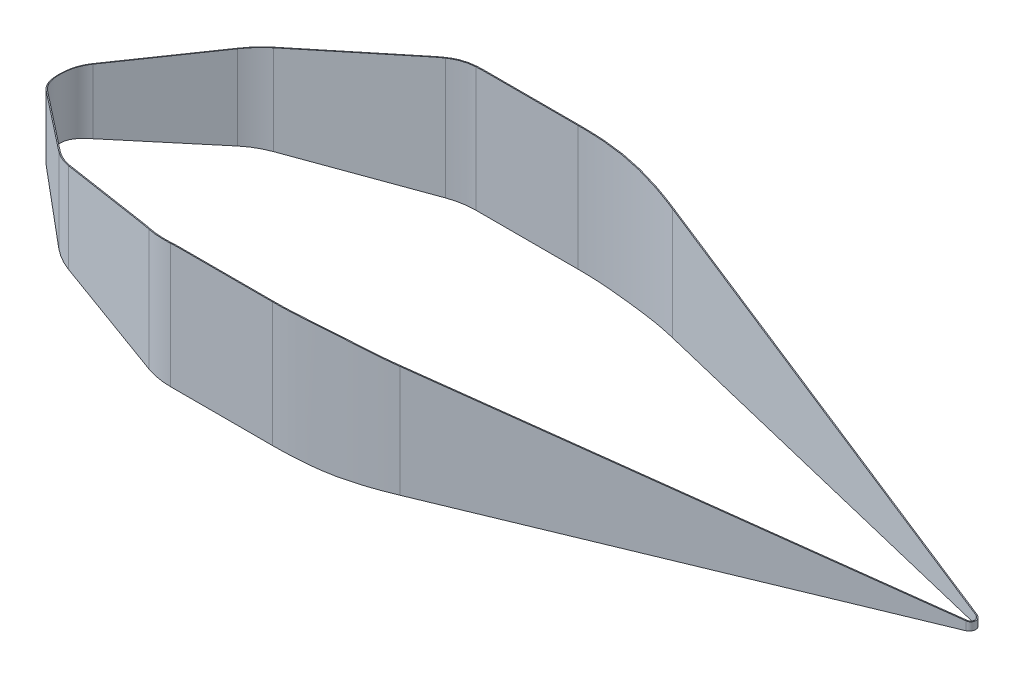
SolidWorks part; units mm, degrees
ref_plane "Front Plane" through (0, 0, 0) normal (0, 0, 1) x (1, 0, 0)
ref_plane "Top Plane" through (0, 0, 0) normal (0, 1, 0) x (1, 0, 0)
ref_plane "Right Plane" through (0, 0, 0) normal (1, 0, 0) x (0, 0, -1)
sketch "Sketch1" plane through (0, 0, 0) normal (0, 1, 0) x (1, 0, 0)
  line L0 (146.0698, 122.5671) -> (556.1483, 466.6637)
  line L1 (676.4552, 536.1229) -> (1335.1737, 775.877)
  line L2 (1471.9818, 800) -> (2005.9909, 800)
  line L3 (2584.2902, 714.5678) -> (4854.922, 28.7185)
  line L4 (4854.922, -28.7185) -> (2584.2902, -714.5678)
  line L5 (2005.9909, -800) -> (1471.9818, -800)
  line L6 (1335.1737, -775.877) -> (676.4552, -536.1229)
  line L7 (556.1483, -466.6637) -> (146.0698, -122.5671)
  arc A0 (146.0698, 122.5671) -> (146.0698, -122.5671) centre (248.9159, 0) ccw
  arc A1 (676.4552, -536.1229) -> (556.1483, -466.6637) centre (813.2633, -160.2459) cw
  arc A2 (1471.9818, -800) -> (1335.1737, -775.877) centre (1471.9818, -400) cw
  arc A3 (1335.1737, 775.877) -> (1471.9818, 800) centre (1471.9818, 400) cw
  arc A4 (556.1483, 466.6637) -> (676.4552, 536.1229) centre (813.2633, 160.2459) cw
  arc A5 (2584.2902, -714.5678) -> (2005.9909, -800) centre (2005.9909, 1200) cw
  arc A6 (2005.9909, 800) -> (2584.2902, 714.5678) centre (2005.9909, -1200) cw
  arc A7 (4854.922, 28.7185) -> (4854.922, -28.7185) centre (4846.2475, 0) cw
  point P11 (0, 0)
  point P14 (610.178, -512)
  point P17 (1401.451, -800)
  point P20 (1401.451, 800)
  point P23 (610.178, 512)
  point P26 (2301.451, -800)
  point P29 (2301.451, 800)
  point P32 (4950, 0)
  dimension "r0" = 160
  dimension "r1" = 400
  dimension "r3" = 2000
  dimension "r4" = 30
  dimension "x1" = 610.178
  dimension "x2" = 1401.451
  dimension "x3" = 2301.451
  dimension "x4" = 4950
  dimension "x5" = 2301.451
  dimension "x6" = 1401.451
  dimension "x7" = 610.178
  dimension "y1" = 512
  dimension "y2" = 800
  dimension "y5" = 800
  dimension "y7" = 512
extrude "TopView_Extrude" add sketch "Sketch1" along normal blind 800
shell "Shell1" thickness 5
sketch "Sketch2" plane through (0, 0, 0) normal (0, 0, 1) x (1, 0, 0)
  line L0 (0, 300) -> (0, 332.8541)
  line L1 (113.6551, 478.3844) -> (1282.1337, 770.2016)
  line L2 (1524.433, 800) -> (2144.4827, 800)
  line L3 (2456.4974, 775.5118) -> (4950, 381.685)
  line L4 (4950, 381.685) -> (4950, 359.158)
  line L5 (4950, 359.158) -> (2419.356, 159.311)
  line L6 (2183.1789, 150) -> (150, 150)
  arc A0 (0, 332.8541) -> (113.6551, 478.3844) centre (150, 332.8541) cw
  arc A1 (0, 300) -> (150, 150) centre (150, 300) ccw
  arc A2 (1282.1337, 770.2016) -> (1524.433, 800) centre (1524.433, -200) cw
  arc A3 (2144.4827, 800) -> (2456.4974, 775.5118) centre (2144.4827, -1200) cw
  arc A4 (2419.356, 159.311) -> (2183.1789, 150) centre (2183.1789, 3150) cw
  point P10 (0, 450)
  point P13 (0, 150)
  point P16 (1401.451, 800)
  point P19 (2301.451, 800)
  point P22 (2301.451, 150)
  dimension "r0" = 150
  dimension "r2" = 1000
  dimension "r3" = 2000
  dimension "r6" = 3000
  dimension "x2" = 1401.451
  dimension "x3" = 2301.451
  dimension "x4" = 4950
  dimension "x6" = 2301.451
  dimension "y0" = 150
  dimension "y1" = 450
  dimension "y2" = 800
  dimension "y4" = 381.685
  dimension "y5" = 359.158
extrude "SideProfile_Cut" cut sketch "Sketch2" against normal through all and the other way through all flip side to cut
